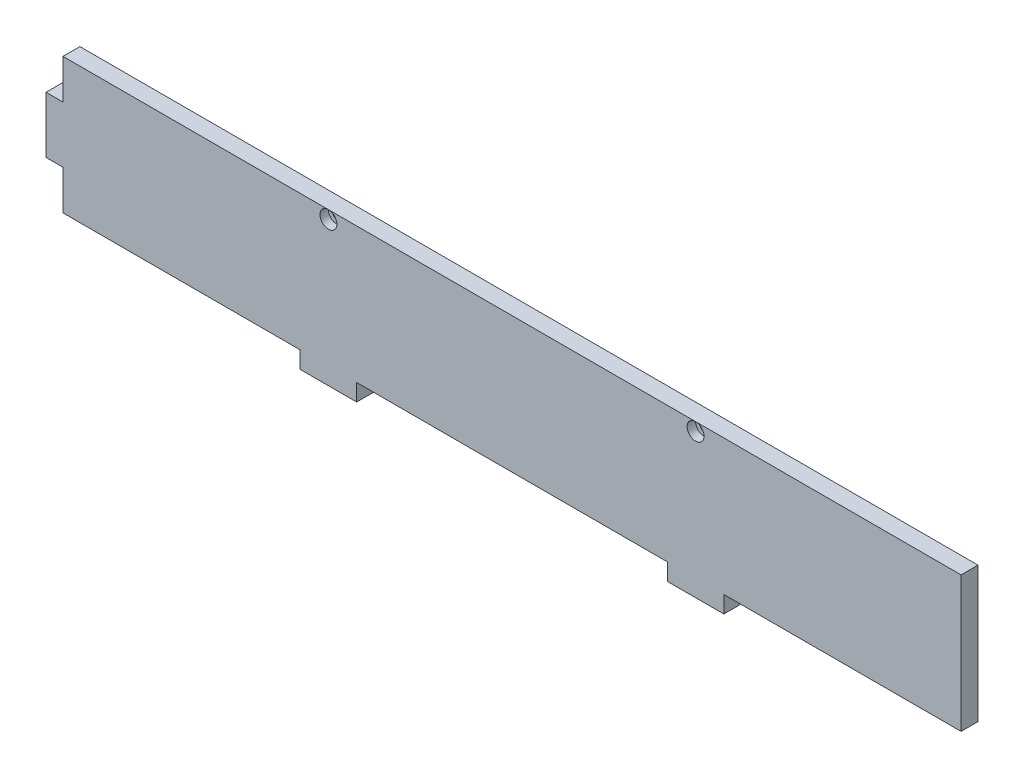
SolidWorks part; units mm, degrees
ref_plane "Plan de face" through (0, 0, 0) normal (0, 0, 1) x (1, 0, 0)
ref_plane "Plan de dessus" through (0, 0, 0) normal (0, 1, 0) x (1, 0, 0)
ref_plane "Plan de droite" through (0, 0, 0) normal (1, 0, 0) x (0, 0, -1)
sketch "Esquisse1" plane through (0, 0, 0) normal (0, 0, 1) x (1, 0, 0)
  line L1 (0, 0) -> (-330, 0)
  line L2 (0, 0) -> (0, 54)
  line L3 (0, 54) -> (-330, 54)
  line L4 (-330, 0) -> (-330, 54)
  dimension "D1" = 330
  dimension "D2" = 54
extrude "Boss.-Extru.1" add sketch "Esquisse1" along normal blind 6
sketch "Esquisse2" plane through (0, 0, 6) normal (0, 0, 1) x (1, 0, 0)
  line L0 (-330, 54) -> (-330, 0) construction
  line L1 (-330, 0) -> (-240, 0)
  line L2 (-330, 0) -> (-330, 20)
  line L3 (-330, 20) -> (-324, 20)
  line L4 (-324, 6) -> (-324, 20)
  line L5 (-330, 0) -> (0, 0) construction
  line L6 (-90, 6) -> (-90, 0)
  line L7 (-324, 40) -> (-324, 54)
  line L8 (-330, 54) -> (-330, 40)
  line L9 (-330, 40) -> (-324, 40)
  line L10 (0, 54) -> (-330, 54) construction
  line L11 (-90, 0) -> (0, 0)
  line L12 (-324, 54) -> (-330, 54)
  line L13 (-324, 6) -> (-240, 6)
  line L14 (-240, 6) -> (-240, 0)
  line L15 (-6, 40) -> (-6, 54)
  line L16 (0, 0) -> (0, 20)
  line L17 (0, 20) -> (-6, 20)
  line L18 (-6, 6) -> (-6, 20)
  line L19 (-6, 54) -> (0, 54)
  line L20 (0, 54) -> (0, 40)
  line L21 (0, 40) -> (-6, 40)
  line L23 (-220, 0) -> (-110, 0)
  line L24 (-220, 0) -> (-220, 6)
  line L25 (-90, 6) -> (-6, 6)
  line L26 (-220, 6) -> (-110, 6)
  line L27 (-110, 0) -> (-110, 6)
  dimension "D1" = 6
  dimension "D2" = 90
  dimension "D3" = 20
  dimension "D4" = 6
  dimension "D5" = 20
  dimension "D6" = 20
  dimension "D7" = 6
  dimension "D8" = 6
  dimension "D9" = 20
  dimension "D10" = 6
  dimension "D11" = 6
  dimension "D12" = 20
  dimension "D13" = 6
  dimension "D14" = 90
  dimension "D15" = 20
extrude "Enlèv. mat.-Extru.1" cut sketch "Esquisse2" against normal through all
sketch "Esquisse3" plane through (0, 0, 6) normal (0, 0, 1) x (1, 0, 0)
  line L0 (-6, 54) -> (-324, 54) construction
  line L1 (-240, 0) -> (-240, 6) construction
  line L2 (-90, 6) -> (-90, 0) construction
  line L3 (-6, 20) -> (-6, 40)
  line L4 (-6, 40) -> (0, 40)
  line L5 (0, 40) -> (0, 20)
  line L6 (0, 20) -> (-6, 20)
  circle A0 centre (-230, 51) radius 1.5
  circle A1 centre (-100, 51) radius 1.5
  dimension "D1" = 3
  dimension "D2" = 3
  dimension "D3" = 10
  dimension "D4" = 3
  dimension "D5" = 3
  dimension "D6" = 10
extrude "Enlèv. mat.-Extru.2" cut sketch "Esquisse3" against normal blind 6
sketch "Esquisse4" plane through (0, 0, 6) normal (0, 0, 1) x (1, 0, 0)
  circle A0 centre (-230, 51) radius 2.995
  circle A1 centre (-100, 51) radius 2.995
  dimension "D1" = 5.99
  dimension "D2" = 5.99
extrude "Enlèv. mat.-Extru.3" cut sketch "Esquisse4" against normal blind 3
